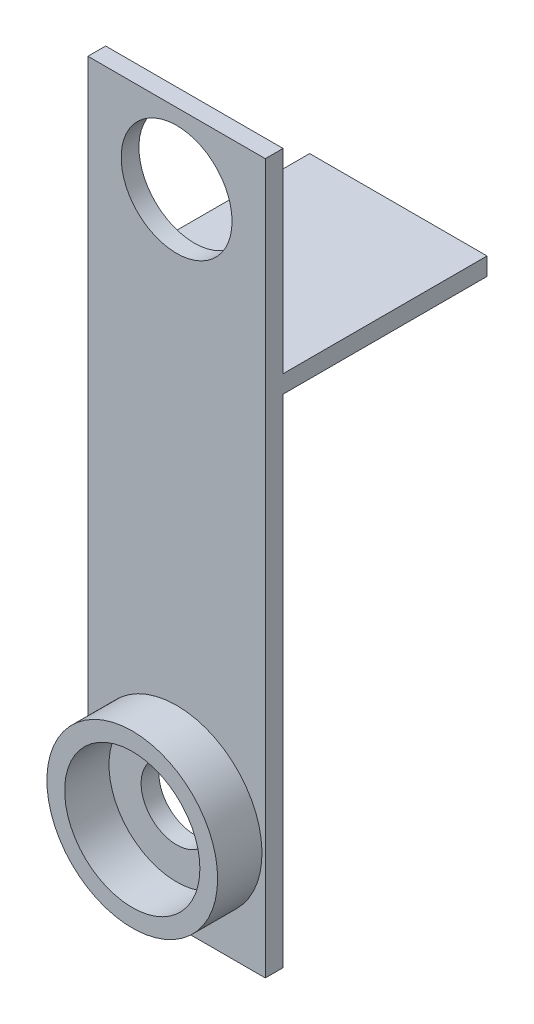
SolidWorks part; units mm, degrees
ref_plane "Front Plane" through (0, 0, 0) normal (0, 0, 1) x (1, 0, 0)
ref_plane "Top Plane" through (0, 0, 0) normal (0, 1, 0) x (1, 0, 0)
ref_plane "Right Plane" through (0, 0, 0) normal (1, 0, 0) x (0, 0, -1)
sketch "Sketch1" plane through (0, 0, 0) normal (1, 0, 0) x (0, 0, -1)
  line L0 (0, 22) -> (0, 0)
  line L1 (0, 0) -> (23, 0)
  line L2 (23, 0) -> (23, -2)
  line L5 (-2, 22) -> (0, 22)
  line L6 (-20.4942, 14) -> (13.6574, 14) construction
  line L7 (-2, 22) -> (-2, -58)
  line L8 (0, -58) -> (0, -2)
  line L9 (0, -2) -> (23, -2)
  line L10 (-2, -58) -> (0, -58)
  dimension "D1" = 80
  dimension "D2" = 22
  dimension "D3" = 2
  dimension "D4" = 2
  dimension "D5" = 8
extrude "Boss-Extrude1" add sketch "Sketch1" along normal blind 20
sketch "Sketch2" plane through (0, 0, 2) normal (0, 0, 1) x (1, 0, 0)
  line L0 (10, 22) -> (10, -58) construction
  line L1 (20, 22) -> (0, 22) construction
  line L2 (-27.7724, -26) -> (46.6406, -26) construction
  line L3 (0, 14) -> (20, 14) construction
  line L4 (0, 22) -> (0, -58) construction
  line L5 (20, 22) -> (20, -58) construction
  line L6 (20, -58) -> (0, -58) construction
  line L7 (-27.7724, -46) -> (50.0359, -46) construction
  circle A0 centre (10, 14) radius 6.25
  circle A1 centre (10, -46) radius 4
  circle A2 centre (10, 14) radius 40 construction
  circle A3 centre (10, -46) radius 20 construction
  dimension "D2" = 12.5
  dimension "D3" = 8
  dimension "D5" = 80
  dimension "D6" = 40
  dimension "D1" = 8
  dimension "D4" = 60
extrude "Cut-Extrude1" cut sketch "Sketch2" against normal blind 15
sketch "Sketch3" plane through (0, 0, 2) normal (0, 0, 1) x (1, 0, 0)
  line L0 (10, 22) -> (10, -58) construction
  line L1 (20, 22) -> (0, 22) construction
  line L2 (20, -58) -> (0, -58) construction
  line L3 (0, 14) -> (20, 14) construction
  line L4 (0, 22) -> (0, -58) construction
  line L5 (20, 22) -> (20, -58) construction
  line L6 (-2.4201, -46) -> (18.1212, -46) construction
  circle A0 centre (10, 14) radius 6 construction
  circle A1 centre (10, -46) radius 7.625
  circle A2 centre (10, -46) radius 9.625
  dimension "D2" = 15.25
  dimension "D1" = 60
  dimension "D3" = 2
extrude "Boss-Extrude2" add sketch "Sketch3" along normal blind 5
